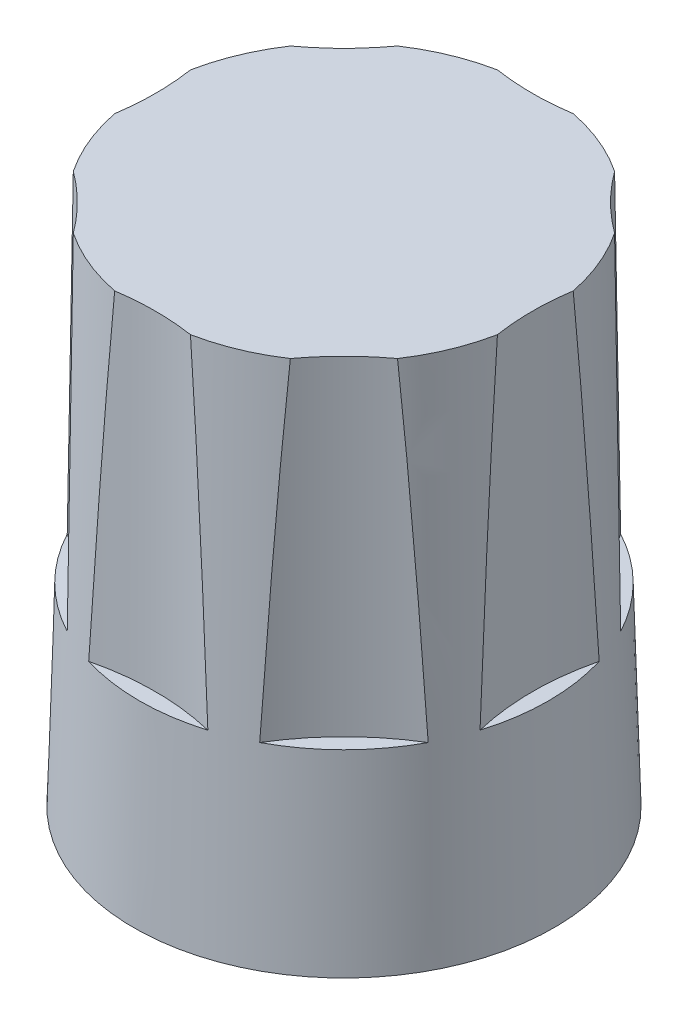
SolidWorks part; units mm, degrees
ref_plane "Front Plane" through (0, 0, 0) normal (0, 0, 1) x (1, 0, 0)
ref_plane "Top Plane" through (0, 0, 0) normal (0, 1, 0) x (1, 0, 0)
ref_plane "Right Plane" through (0, 0, 0) normal (1, 0, 0) x (0, 0, -1)
sketch "Sketch1" plane through (0, 0, 0) normal (0, 0, 1) x (1, 0, 0)
  line L0 (-6.375, 0) -> (-5.92, 15.88)
  line L1 (-5.92, 15.88) -> (0, 15.88)
  line L2 (0, 15.88) -> (0, 14.88)
  line L3 (0, 14.88) -> (-4.4487, 14.88)
  line L4 (-4.4487, 14.88) -> (-4.875, 0)
  line L5 (-4.875, 0) -> (-6.375, 0)
  line L6 (0, 0) -> (0, 5.95) construction
  dimension "D1" = 12.75
  dimension "D2" = 1.5
  dimension "D3" = 11.84
  dimension "D4" = 15.88
  dimension "D5" = 14.88
revolve "Revolve1" add sketch "Sketch1" angle 360 about L6
sketch "Sketch2" plane through (0, 15.88, 0) normal (0, 1, 0) x (1, 0, 0)
  line L0 (0, 0) -> (-13.3443, 0) construction
  line L1 (-5.8072, 1.15) -> (-5.8072, -1.15) construction
  circle A0 centre (-13.3443, 0) radius 7.6243
  circle A1 centre (0, 0) radius 5.92 construction
  circle A2 centre (0, 0) radius 5.92 construction
  point P9 (-5.72, 0)
  point P10 (-5.92, 0)
  dimension "D1" = 2.3
  dimension "D2" = 0.2
extrude "Cut-Extrude1" cut sketch "Sketch2" against normal blind 10
pattern_circular "CirPattern1" count 8 over 360 about axis through (0, 0, 0) along (0, 1, 0) of "Cut-Extrude1"
sketch "Sketch3" plane through (0, 14.88, 0) normal (0, -1, 0) x (1, 0, 0)
  line L0 (-3.27, 0) -> (0, 0) construction
  line L1 (-4.875, 0.41) -> (-3.27, 0.41)
  line L2 (-4.875, 0.41) -> (-4.875, -0.41)
  line L3 (-4.875, -0.41) -> (-3.27, -0.41)
  line L4 (-3.27, 0.41) -> (-3.27, -0.41)
  line L5 (-4.0169, 2.7926) -> (-2.6269, 1.9901)
  line L6 (-4.0169, 2.7926) -> (-4.4269, 2.0824)
  line L7 (-4.4269, 2.0824) -> (-3.0369, 1.2799)
  line L8 (-2.6269, 1.9901) -> (-3.0369, 1.2799)
  line L9 (-2.0824, 4.4269) -> (-1.2799, 3.0369)
  line L10 (-2.0824, 4.4269) -> (-2.7926, 4.0169)
  line L11 (-2.7926, 4.0169) -> (-1.9901, 2.6269)
  line L12 (-1.2799, 3.0369) -> (-1.9901, 2.6269)
  line L13 (0.41, 4.875) -> (0.41, 3.27)
  line L14 (0.41, 4.875) -> (-0.41, 4.875)
  line L15 (-0.41, 4.875) -> (-0.41, 3.27)
  line L16 (0.41, 3.27) -> (-0.41, 3.27)
  line L17 (2.7926, 4.0169) -> (1.9901, 2.6269)
  line L18 (2.7926, 4.0169) -> (2.0824, 4.4269)
  line L19 (2.0824, 4.4269) -> (1.2799, 3.0369)
  line L20 (1.9901, 2.6269) -> (1.2799, 3.0369)
  line L21 (4.4269, 2.0824) -> (3.0369, 1.2799)
  line L22 (4.4269, 2.0824) -> (4.0169, 2.7926)
  line L23 (4.0169, 2.7926) -> (2.6269, 1.9901)
  line L24 (3.0369, 1.2799) -> (2.6269, 1.9901)
  line L25 (4.875, -0.41) -> (3.27, -0.41)
  line L26 (4.875, -0.41) -> (4.875, 0.41)
  line L27 (4.875, 0.41) -> (3.27, 0.41)
  line L28 (3.27, -0.41) -> (3.27, 0.41)
  line L29 (4.0169, -2.7926) -> (2.6269, -1.9901)
  line L30 (4.0169, -2.7926) -> (4.4269, -2.0824)
  line L31 (4.4269, -2.0824) -> (3.0369, -1.2799)
  line L32 (2.6269, -1.9901) -> (3.0369, -1.2799)
  line L33 (2.0824, -4.4269) -> (1.2799, -3.0369)
  line L34 (2.0824, -4.4269) -> (2.7926, -4.0169)
  line L35 (2.7926, -4.0169) -> (1.9901, -2.6269)
  line L36 (1.2799, -3.0369) -> (1.9901, -2.6269)
  line L37 (-0.41, -4.875) -> (-0.41, -3.27)
  line L38 (-0.41, -4.875) -> (0.41, -4.875)
  line L39 (0.41, -4.875) -> (0.41, -3.27)
  line L40 (-0.41, -3.27) -> (0.41, -3.27)
  line L41 (-2.7926, -4.0169) -> (-1.9901, -2.6269)
  line L42 (-2.7926, -4.0169) -> (-2.0824, -4.4269)
  line L43 (-2.0824, -4.4269) -> (-1.2799, -3.0369)
  line L44 (-1.9901, -2.6269) -> (-1.2799, -3.0369)
  line L45 (-4.4269, -2.0824) -> (-3.0369, -1.2799)
  line L46 (-4.4269, -2.0824) -> (-4.0169, -2.7926)
  line L47 (-4.0169, -2.7926) -> (-2.6269, -1.9901)
  line L48 (-3.0369, -1.2799) -> (-2.6269, -1.9901)
  circle A0 centre (0, 0) radius 4.875 construction
  point P56 (0, 0)
  dimension "D1" = 3.27
  dimension "D2" = 0.82
  dimension "D3" = 12
extrude "Boss-Extrude1" add sketch "Sketch3" along normal up to surface (14.88 mm away) up to face at (0, 0, -4.875)
